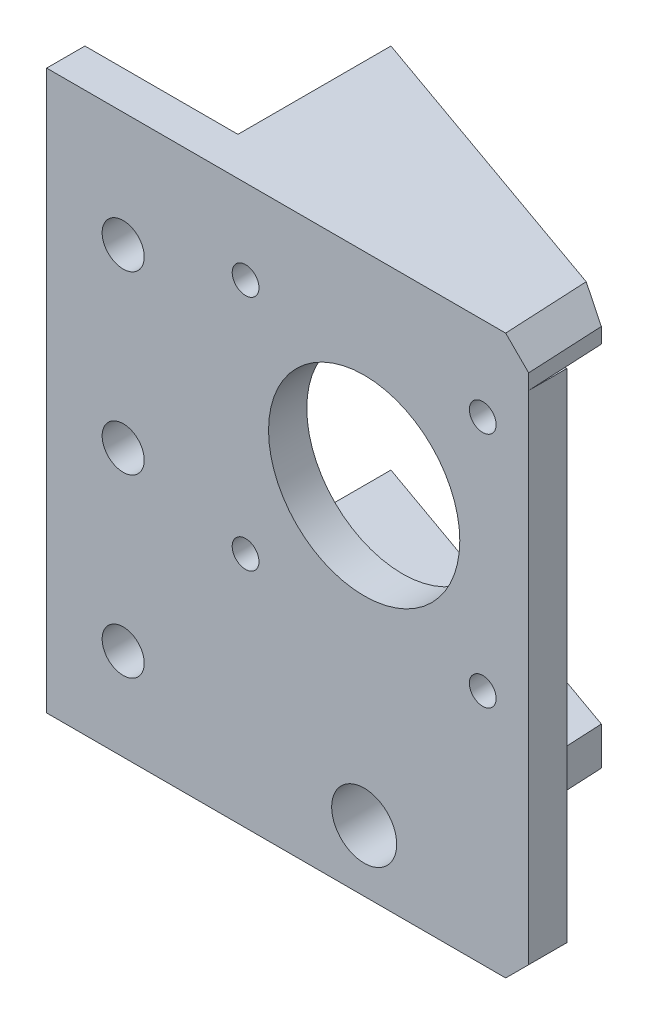
SolidWorks part; units mm, degrees
ref_plane "前视基准面" through (0, 0, 0) normal (0, 0, 1) x (1, 0, 0)
ref_plane "上视基准面" through (0, 0, 0) normal (0, 1, 0) x (1, 0, 0)
ref_plane "右视基准面" through (0, 0, 0) normal (1, 0, 0) x (0, 0, -1)
sketch "草图2" plane through (0, 0, 0) normal (0, 0, 1) x (1, 0, 0)
  line L0 (23.028, -31.0315) -> (23.028, 11.9685) construction
  line L1 (-19.972, 11.9685) -> (43.028, 11.9685)
  line L2 (-19.972, 11.9685) -> (-19.972, -31.0315)
  line L3 (-19.972, -31.0315) -> (43.028, -31.0315)
  line L4 (43.028, 11.9685) -> (43.028, -31.0315)
  line L5 (-19.972, 11.9685) -> (43.028, -31.0315) construction
  line L6 (-19.972, -31.0315) -> (43.028, 11.9685) construction
  line L7 (23.028, -9.5315) -> (-19.972, -9.5315) construction
  line L8 (33.028, -31.0315) -> (33.028, 11.9685) construction
  line L9 (-13.972, 5.9685) -> (17.028, 5.9685) construction
  line L10 (-13.972, 5.9685) -> (-13.972, -25.0315) construction
  line L11 (-13.972, -25.0315) -> (17.028, -25.0315) construction
  line L12 (17.028, 5.9685) -> (17.028, -25.0315) construction
  line L13 (1.528, -25.0315) -> (1.528, 5.9685) construction
  line L14 (-13.972, -9.5315) -> (17.028, -9.5315) construction
  circle A0 centre (-13.972, 5.9685) radius 1.75
  circle A1 centre (17.028, 5.9685) radius 1.75
  circle A2 centre (17.028, -25.0315) radius 1.75
  circle A3 centre (-13.972, -25.0315) radius 1.75
  circle A4 centre (1.528, -9.5315) radius 12.5
  circle A5 centre (33.028, 1.9685) radius 2.75
  circle A6 centre (33.028, -21.0315) radius 2.75
  point P4 (11.528, -9.5315)
  point P9 (1.528, -9.5315)
  dimension "D6" = 25
  dimension "D7" = 3.5
  dimension "D8" = 5.5
  dimension "D9" = 5.5
  dimension "D1" = 63
  dimension "D2" = 43
  dimension "D3" = 43
  dimension "D4" = 31
  dimension "D5" = 31
  dimension "D10" = 10
  dimension "D11" = 10
  dimension "D12" = 10
extrude "凸台-拉伸1" add sketch "草图2" along normal blind 5
sketch "草图3" plane through (0, -31.0315, 0) normal (0, -1, 0) x (1, 0, 0)
  line L4 (-19.972, 0) -> (43.028, 0)
  line L5 (43.028, 0) -> (43.028, 5)
  line L6 (43.028, 5) -> (-19.972, 5)
  line L7 (-19.972, 5) -> (-19.972, 0)
  line L8 (-19.972, 0) -> (43.028, 0)
  line L9 (43.028, 0) -> (43.028, 5)
  line L10 (43.028, 5) -> (-19.972, 5)
  line L11 (-19.972, 5) -> (-19.972, 0)
  dimension "D1" = 0
extrude "凸台-拉伸2" add sketch "草图3" along normal blind 25
sketch "草图4" plane through (0, 0, 5) normal (0, 0, 1) x (1, 0, 0)
  line L0 (1.528, -9.5315) -> (1.528, -56.0315) construction
  line L1 (43.028, -56.0315) -> (-19.972, -56.0315) construction
  circle A0 centre (1.528, -48.0315) radius 4.25
  dimension "D1" = 8.5
  dimension "D2" = 8
extrude "切除-拉伸2" cut sketch "草图4" against normal blind 25
sketch "草图5" plane through (0, 0, 0) normal (0, 0, -1) x (-1, 0, 0)
  circle A0 centre (-1.528, -48.0315) radius 7.75
  circle A1 centre (-1.528, -48.0315) radius 4.25
  dimension "D2" = 3.5
extrude "凸台-拉伸3" add sketch "草图5" along normal blind 10
sketch "草图7" plane through (0, 11.9685, 0) normal (0, 1, 0) x (1, 0, 0)
  line L0 (-19.972, -5) -> (-19.472, 5)
  line L1 (-19.472, 0) -> (-19.472, 40) construction
  line L2 (-19.472, 5) -> (23.028, 20)
  line L3 (23.028, 20) -> (23.028, -5)
  line L4 (43.028, -5) -> (-19.972, -5) construction
  line L5 (23.028, -5) -> (-19.972, -5)
  line L6 (43.028, -5) -> (43.028, 0) construction
  dimension "D1" = 10
  dimension "D2" = 25
  dimension "D3" = 20
extrude "凸台-拉伸4" add sketch "草图7" along normal blind 5
ref_plane "基准面1" through (0, -31.0315, 0) normal (0, -1, 0) x (-1, 0, 0)
sketch "草图8" plane through (0, -31.0315, 0) normal (0, -1, 0) x (-1, 0, 0)
  line L4 (-23.028, 20) -> (-23.028, 0)
  line L5 (-23.028, 0) -> (19.722, 0)
  line L6 (19.722, 0) -> (19.472, 5)
  line L7 (19.472, 5) -> (-23.028, 20)
  line L8 (-23.028, 20) -> (-23.028, 0)
  line L9 (-23.028, 0) -> (19.722, 0)
  line L10 (19.722, 0) -> (19.472, 5)
  line L11 (19.472, 5) -> (-23.028, 20)
  dimension "D1" = 0
extrude "凸台-拉伸5" add sketch "草图8" along normal blind 5
sketch "草图10" plane through (0, 0, 5) normal (0, 0, 1) x (1, 0, 0)
  line L0 (33.028, -21.0315) -> (33.028, -56.0315) construction
  line L1 (43.028, -56.0315) -> (-19.972, -56.0315) construction
  circle A0 centre (33.028, -44.0315) radius 2.75
  dimension "D2" = 5.5
  dimension "D1" = 12
extrude "切除-拉伸3" cut sketch "草图10" against normal through all
sketch "草图11" plane through (0, 11.9685, 0) normal (0, 1, 0) x (1, 0, 0)
  line L4 (23.028, 0) -> (23.028, -5)
  line L5 (23.028, -5) -> (43.028, -5)
  line L6 (43.028, -5) -> (43.028, 0)
  line L7 (43.028, 0) -> (23.028, 0)
  line L8 (23.028, 0) -> (23.028, -5)
  line L9 (23.028, -5) -> (43.028, -5)
  line L10 (43.028, -5) -> (43.028, 0)
  line L11 (43.028, 0) -> (23.028, 0)
  dimension "D1" = 0
extrude "凸台-拉伸6" add sketch "草图11" along normal blind 5
chamfer "倒角1" distance 3 angle 45 2 edges at (-19.722, 16.9685, 0) (-19.972, -56.0315, 2.5)
mirror "镜向2" about plane through (43.028, 11.9685, 5) normal (-1, 0, 0) of bodies 109
delete or keep bodies "实体-删除/保留 1" type keep bodies bodies 111
